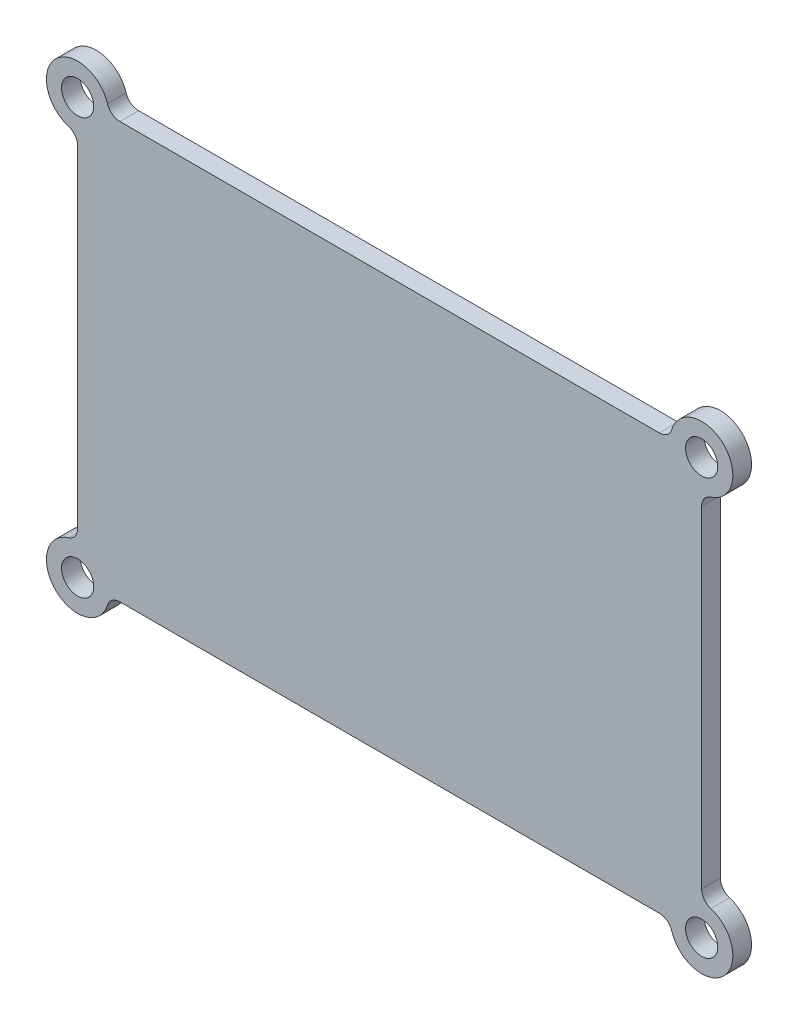
SolidWorks part; units mm, degrees
ref_plane "前视基准面" through (0, 0, 0) normal (0, 0, 1) x (1, 0, 0)
ref_plane "上视基准面" through (0, 0, 0) normal (0, 1, 0) x (1, 0, 0)
ref_plane "右视基准面" through (0, 0, 0) normal (1, 0, 0) x (0, 0, -1)
other "Configuration Table"
sketch "草图1" plane through (0, 0, 0) normal (0, 0, 1) x (1, 0, 0)
  line L0 (0, 40) -> (58.7103, 0.8598) construction
  line L5 (-30, -20) -> (30, 20) construction
  line L6 (0, 40) -> (58.7103, 0.8598) construction
  line L7 (0, 0) -> (60, 40) construction
  line L8 (4.062, 40) -> (55.938, 40)
  line L9 (0, 38.45) -> (0, 40)
  line L10 (0, 4.062) -> (0, 35.938)
  line L11 (4.062, 0) -> (55.938, 0)
  line L13 (60, 4.062) -> (60, 35.938)
  line L14 (60, 0) -> (892.0503, -554.7002) construction
  circle A0 centre (0, 40) radius 1.55
  circle A1 centre (60, 40) radius 1.55
  circle A2 centre (60, 0) radius 1.55
  circle A3 centre (0, 0) radius 1.55
  arc A4 (-0.8824, 2.8673) -> (2.8673, -0.8824) centre (0, 0) ccw
  arc A5 (57.1327, -0.8824) -> (60.8824, 2.8673) centre (60, 0) ccw
  arc A6 (60.8824, 37.1327) -> (57.1327, 40.8824) centre (60, 40) ccw
  arc A7 (2.8673, 40.8824) -> (-0.8824, 37.1327) centre (0, 40) ccw
  arc A8 (2.8673, 40.8824) -> (4.062, 40) centre (4.062, 41.25) ccw
  arc A9 (55.938, 40) -> (57.1327, 40.8824) centre (55.938, 41.25) ccw
  arc A10 (60.8824, 37.1327) -> (60, 35.938) centre (61.25, 35.938) ccw
  arc A11 (60, 4.062) -> (60.8824, 2.8673) centre (61.25, 4.062) ccw
  arc A12 (57.1327, -0.8824) -> (55.938, 0) centre (55.938, -1.25) ccw
  arc A13 (4.062, 0) -> (2.8673, -0.8824) centre (4.062, -1.25) ccw
  arc A14 (-0.8824, 2.8673) -> (0, 4.062) centre (-1.25, 4.062) ccw
  arc A15 (0, 35.938) -> (-0.8824, 37.1327) centre (-1.25, 35.938) ccw
  point P4 (30, 20)
  dimension "D3" = 3.1
  dimension "D4" = 6
  dimension "D5" = 2.5
  dimension "D1" = 40
  dimension "D2" = 60
extrude "凸台-拉伸1" add sketch "草图1" along normal blind 1.8 contours A15 L10 A14 A4 A13 L11 A12 A5 A11 L13 A10 A6 A9 L8 A8 A7 A3 A2 A1 A0
